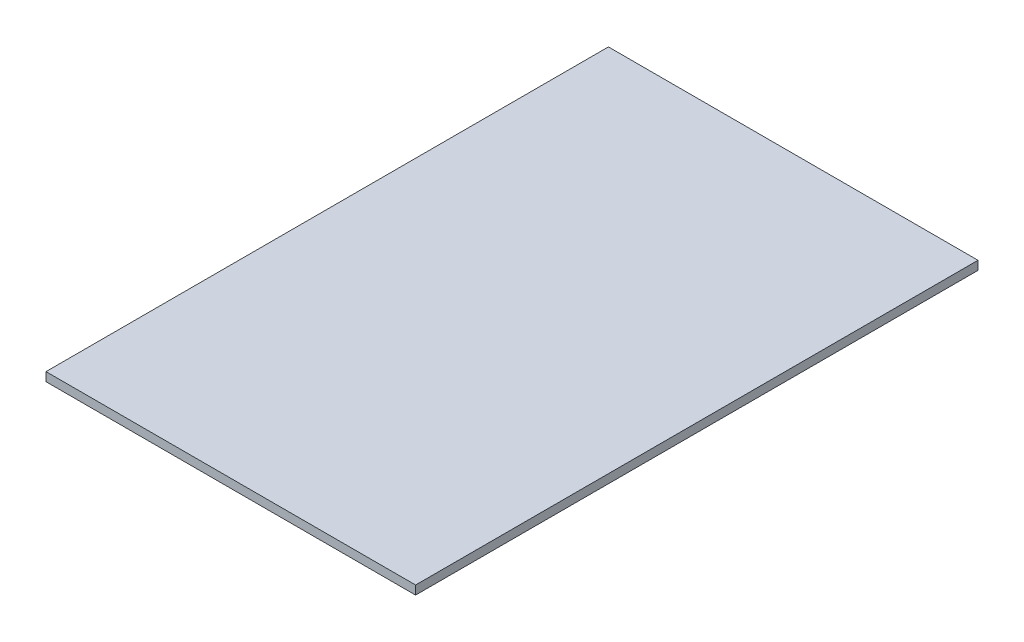
SolidWorks part; units mm, degrees
material "Acrylic (Medium-high impact)"
ref_plane "Front Plane" through (0, 0, 0) normal (0, 0, 1) x (1, 0, 0)
ref_plane "Top Plane" through (0, 0, 0) normal (0, 1, 0) x (1, 0, 0)
ref_plane "Right Plane" through (0, 0, 0) normal (1, 0, 0) x (0, 0, -1)
sketch "Sketch1" plane through (0, 0, 0) normal (0, 1, 0) x (1, 0, 0)
  line L0 (63.25, -96.25) -> (63.25, 96.25)
  line L1 (57.75, -90.75) -> (-57.75, -90.75) construction
  line L2 (57.75, -90.75) -> (57.75, 90.75) construction
  line L3 (57.75, 90.75) -> (-57.75, 90.75) construction
  line L4 (-57.75, -90.75) -> (-57.75, 90.75) construction
  line L5 (57.75, -90.75) -> (-57.75, 90.75) construction
  line L6 (57.75, 90.75) -> (-57.75, -90.75) construction
  line L7 (63.25, 96.25) -> (-63.25, 96.25)
  line L8 (-63.25, -96.25) -> (-63.25, 96.25)
  line L9 (63.25, -96.25) -> (-63.25, -96.25)
  point P0 (0, 0)
  dimension "D1" = 115.5
  dimension "D2" = 181.5
  dimension "D3" = 5.5
extrude "Boss-Extrude1" add sketch "Sketch1" along normal blind 3
sketch "Sketch2" [suppressed] plane through (0, 3, 0) normal (0, 1, 0) x (1, 0, 0)
  line L0 (0, 0) -> (50000, 0) construction
  line L1 (0, 0) -> (0, 31.9259) construction
  circle A0 centre (67, 0) radius 7.5
  circle A1 centre (-67, 0) radius 7.5
  dimension "D1" = 15
  dimension "D2" = 67
